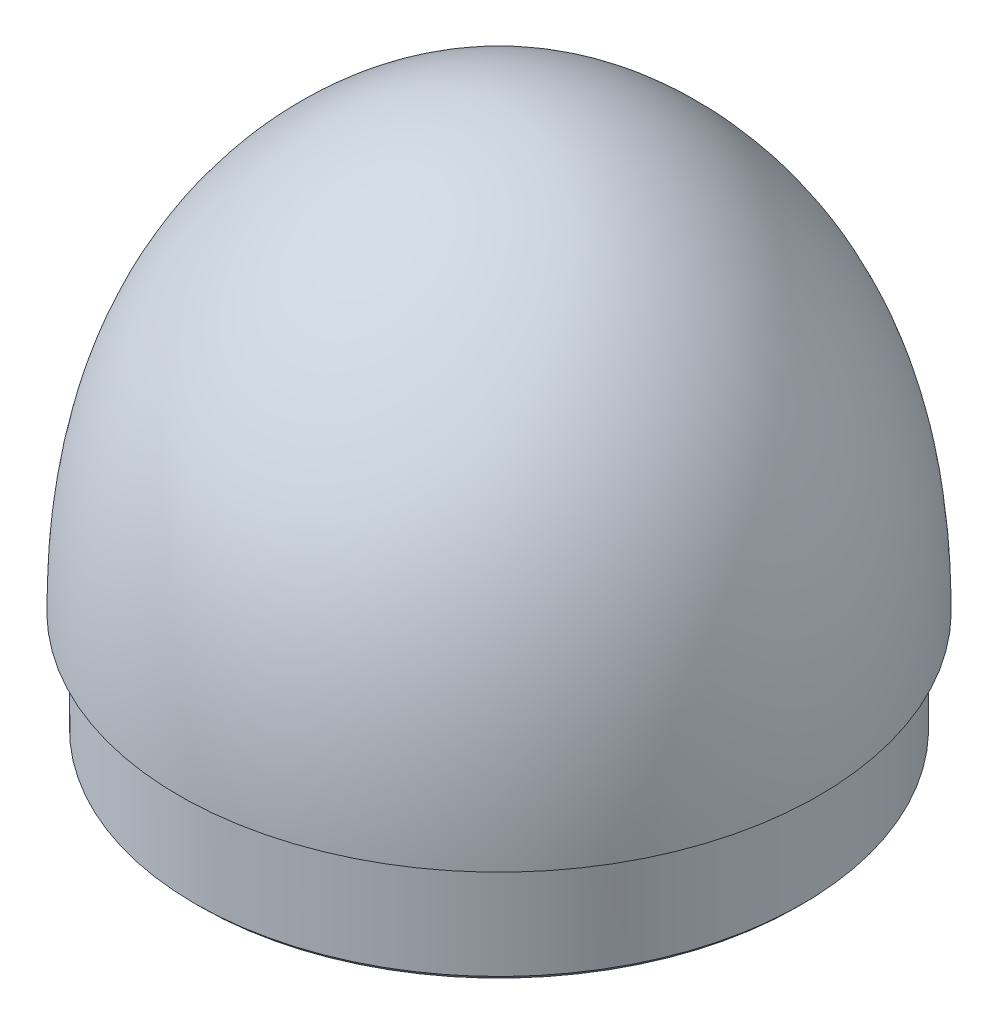
SolidWorks part; units mm, degrees
ref_plane "Front Plane" through (0, 0, 0) normal (0, 0, 1) x (1, 0, 0)
ref_plane "Top Plane" through (0, 0, 0) normal (0, 1, 0) x (1, 0, 0)
ref_plane "Right Plane" through (0, 0, 0) normal (1, 0, 0) x (0, 0, -1)
sketch "Sketch3" plane through (0, 0, 0) normal (0, 0, 1) x (1, 0, 0)
  line L0 (0, 0) -> (0, 77.7068) construction
  line L1 (0, 0) -> (-48.9715, 0) construction
  line L2 (-41.25, 0) -> (-42.75, 0)
  line L3 (-42.75, 0) -> (-42.75, 15)
  line L5 (-41.25, 15) -> (-41.25, 0)
  line L6 (-42.75, 15) -> (-45, 15)
  line L7 (-45, 15) -> (-45, 57.5369) construction
  line L8 (-45, 29.9096) -> (-45, 0.0904) construction
  line L9 (0, 76.0474) -> (-12.9328, 76.0474) construction
  line L10 (9.8415, 76.0474) -> (-9.8415, 76.0474) construction
  line L11 (-42.75, 16.5) -> (-43.4904, 16.5)
  line L12 (0, 76.0474) -> (0, 74.5474)
  line L13 (-42.75, 16.5) -> (-41.25, 16.5)
  line L14 (-41.25, 16.5) -> (-41.25, 15)
  spline S0 degree 3 poles (-45, 15) (-45, 33.637) (-37.6231, 59.4848) (-12.3019, 76.0474) (0, 76.0474) knots 0 0 0 0 0.58489 1 1 1 1
  spline S1 degree 1 poles (-43.4904, 16.5) (0, 74.5474) knots 0 0 1 1 construction
  spline S2 degree 3 poles (-43.4904, 16.5) (-43.4783, 17.4474) (-43.4297, 19.3558) (-43.2359, 23.0569) (-42.8079, 27.5456) (-41.9866, 32.6895) (-40.4667, 39.238) (-37.743, 46.8477) (-33.8424, 53.7284) (-29.961, 58.8167) (-25.5475, 63.6462) (-20.3932, 67.9041) (-14.6199, 71.1835) (-10.0105, 73.0597) (-5.952, 74.0596) (-2.5946, 74.4754) (-0.861, 74.5474) (0, 74.5474) knots 0.015976 0.015976 0.015976 0.015976 0.046726 0.077477 0.138979 0.20048 0.261982 0.384985 0.507988 0.569489 0.630991 0.753994 0.815495 0.876997 0.938498 0.969249 1 1 1 1
  dimension "D1" = 42.75
  dimension "D2" = 1.5
  dimension "D3" = 15
  dimension "D4" = 2.25
  dimension "D5" = 1.5
revolve "Revolve1" add sketch "Sketch3" angle 360 about L0
sketch "Sketch4" plane through (0, 0, 0) normal (0, -1, 0) x (1, 0, 0)
  line L0 (-41.25, 0) -> (41.25, 0) construction
  line L1 (0, 0) -> (0, 41.25) construction
  line L2 (-41.0556, 4) -> (-4, 4)
  line L3 (-4, 4) -> (-4, 41.0556)
  line L4 (-4, -4) -> (-4, -41.0556)
  line L5 (-41.0556, -4) -> (-4, -4)
  line L6 (4, -4) -> (4, -41.0556)
  line L7 (41.0556, -4) -> (4, -4)
  line L8 (41.0556, 4) -> (4, 4)
  line L9 (4, 4) -> (4, 41.0556)
  circle A0 centre (0, 0) radius 41.25 construction
  arc A1 (-41.0556, 4) -> (-41.0556, -4) centre (0, 0) ccw
  arc A2 (4, 41.0556) -> (-4, 41.0556) centre (0, 0) ccw
  arc A3 (41.0556, -4) -> (41.0556, 4) centre (0, 0) ccw
  arc A4 (-4, -41.0556) -> (4, -41.0556) centre (0, 0) ccw
  point P10 (-3.4593, 41.1047)
  point P11 (-41.1585, 2.7457)
  dimension "D1" = 8
  dimension "D2" = 8
extrude "Boss-Extrude2" add sketch "Sketch4" against normal blind 5
chamfer "Chamfer1" distance 0.7 angle 45 1 edges at (0, 0, -42.75)
fillet "Fillet1" radius 2 16 edges at (22.5278, 5, -4) (4, 5, -22.5278) (-4, 5, -22.5278) (-22.5278, 5, -4) (-22.5278, 5, 4) (-4, 5, 22.5278) (4, 5, 22.5278) (22.5278, 5, 4) (22.5278, 0, -4) (4, 0, -22.5278) (-4, 0, -22.5278) (-22.5278, 0, -4) (-22.5278, 0, 4) (22.5278, 0, 4) (4, 0, 22.5278) (-4, 0, 22.5278)
